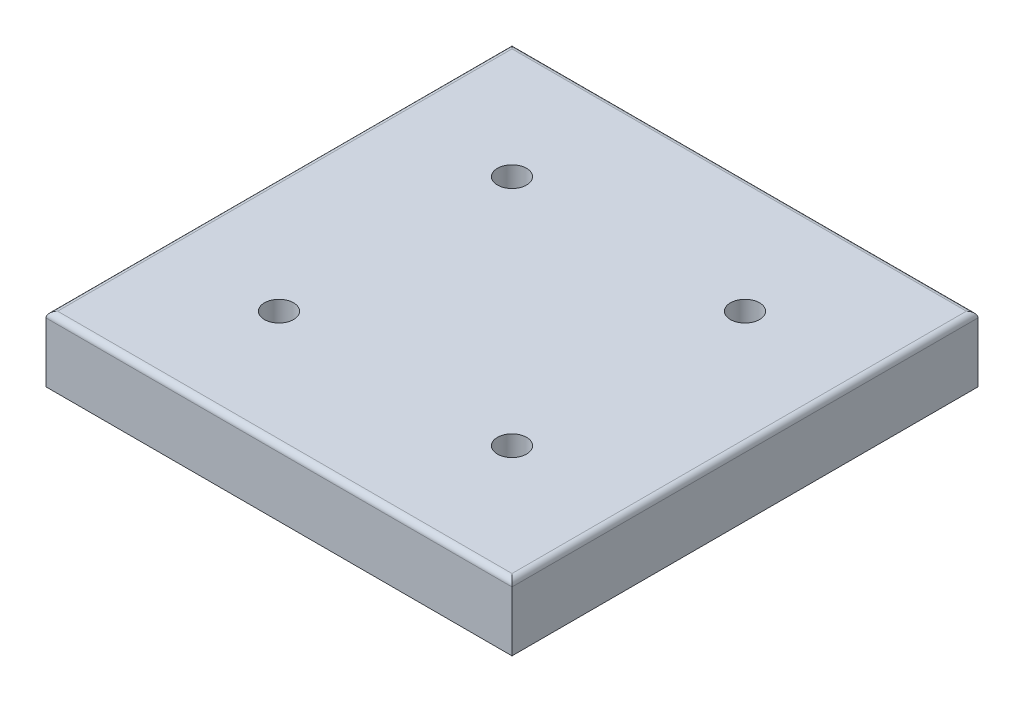
SolidWorks part; units mm, degrees
ref_plane "前视基准面" through (0, 0, 0) normal (0, 0, 1) x (1, 0, 0)
ref_plane "上视基准面" through (0, 0, 0) normal (0, 1, 0) x (1, 0, 0)
ref_plane "右视基准面" through (0, 0, 0) normal (1, 0, 0) x (0, 0, -1)
sketch "草图1" plane through (0, 0, 0) normal (0, 1, 0) x (1, 0, 0)
  line L1 (0, 0) -> (160, 0)
  line L2 (0, 0) -> (0, 160)
  line L3 (0, 160) -> (160, 160)
  line L4 (160, 0) -> (160, 160)
  dimension "D1" = 160
  dimension "D2" = 160
extrude "凸台-拉伸1" add sketch "草图1" along normal blind 22.5
sketch "草图2" plane through (0, 22.5, 0) normal (0, 1, 0) x (1, 0, 0)
  line L0 (0, 160) -> (0, 0) construction
  line L3 (160, 160) -> (0, 160) construction
  circle A0 centre (40, 120) radius 5
  dimension "D3" = 10
  dimension "D1" = 40
  dimension "D2" = 40
extrude "切除-拉伸1" cut sketch "草图2" against normal through all
pattern_linear "阵列(线性)1" count 2 spacing 80 along (1, 0, 0) count 2 spacing 80 along (0, 0, 1) of "切除-拉伸1"
fillet "圆角2" radius 2 4 edges at (0, 22.5, -80) (80, 22.5, 0) (160, 22.5, -80) (80, 22.5, -160)
